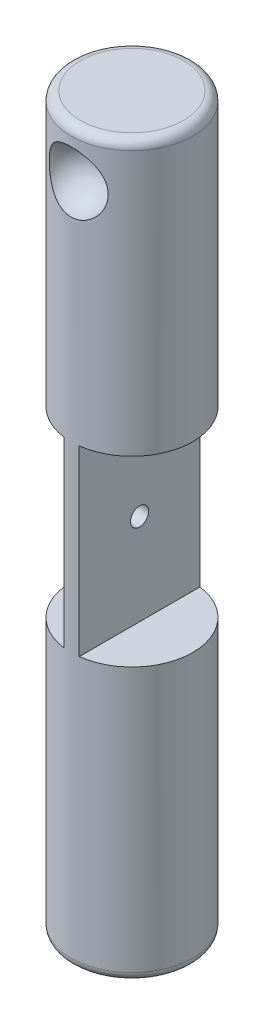
SolidWorks part; units mm, degrees
ref_plane "Front Plane" through (0, 0, 0) normal (0, 0, 1) x (1, 0, 0)
ref_plane "Top Plane" through (0, 0, 0) normal (0, 1, 0) x (1, 0, 0)
ref_plane "Right Plane" through (0, 0, 0) normal (1, 0, 0) x (0, 0, -1)
sketch "Sketch1" plane through (0, 0, 0) normal (0, 1, 0) x (1, 0, 0)
  circle A0 centre (0, 0) radius 20
  dimension "D1" = 40
extrude "Boss-Extrude1" add sketch "Sketch1" along normal mid plane 240
sketch "Sketch2" plane through (0, 0, 0) normal (0, 0, 1) x (1, 0, 0)
  line L0 (-20, 120) -> (-20, -120) construction
  line L1 (-20, 30) -> (-2.5, 30)
  line L2 (-20, 30) -> (-20, -30)
  line L3 (-20, -30) -> (-2.5, -30)
  line L4 (-2.5, 30) -> (-2.5, -30)
  line L5 (0, 120) -> (0, -120) construction
  line L6 (27.3901, 30) -> (2.5, 30)
  line L7 (27.3901, 30) -> (27.3901, -30)
  line L8 (27.3901, -30) -> (2.5, -30)
  line L9 (2.5, 30) -> (2.5, -30)
  line L10 (20, 120) -> (-20, 120) construction
  line L11 (-20, -120) -> (20, -120) construction
  point P16 (-2.5, 0)
  point P17 (2.5, 0)
  point P19 (27.3901, 0)
  dimension "D1" = 60
  dimension "D2" = 2.5
  dimension "D3" = 5
extrude "Cut-Extrude5" cut sketch "Sketch2" against normal through all both and the other way through all
sketch "Sketch6" plane through (2.5, 0, 0) normal (1, 0, 0) x (0, 0, -1)
  circle A0 centre (0, 0) radius 3
  dimension "D1" = 6
extrude "Cut-Extrude7" cut sketch "Sketch6" against normal through all both and the other way through all
sketch "Sketch7" plane through (0, 0, 0) normal (1, 0, 0) x (0, 0, -1)
  line L0 (-20, 120) -> (-20, -120) construction
  line L1 (-30, 104) -> (-10, 104)
  arc A0 (-30, 104) -> (-10, 104) centre (-20, 104) ccw
  dimension "D1" = 20
  dimension "D2" = 104
revolve "Cut-Revolve1" cut sketch "Sketch7" angle 360 about L1
fillet "Fillet1" radius 3 2 edges at (0, -120, 20) (0, 120, 20)
